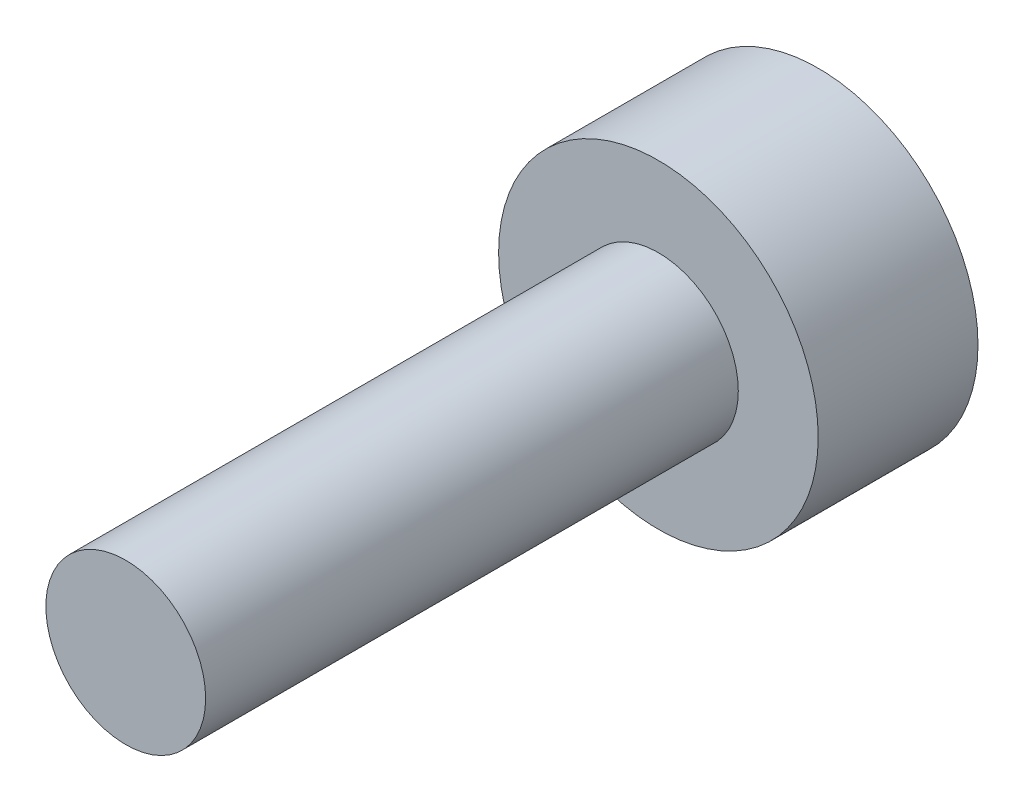
SolidWorks part; units mm, degrees
ref_plane "Front Plane" through (0, 0, 0) normal (0, 0, 1) x (1, 0, 0)
ref_plane "Top Plane" through (0, 0, 0) normal (0, 1, 0) x (1, 0, 0)
ref_plane "Right Plane" through (0, 0, 0) normal (1, 0, 0) x (0, 0, -1)
sketch "Sketch1" plane through (0, 0, 0) normal (0, 0, 1) x (1, 0, 0)
  circle A0 centre (-1.8495, 0.4256) radius 1.5
  dimension "D1" = 3
extrude "Boss-Extrude1" add sketch "Sketch1" along normal blind 10
sketch "Sketch2" plane through (0, 0, 0) normal (0, 0, -1) x (-1, 0, 0)
  circle A0 centre (1.8495, 0.4256) radius 3
  dimension "D1" = 6
extrude "Boss-Extrude2" add sketch "Sketch2" along normal blind 3
